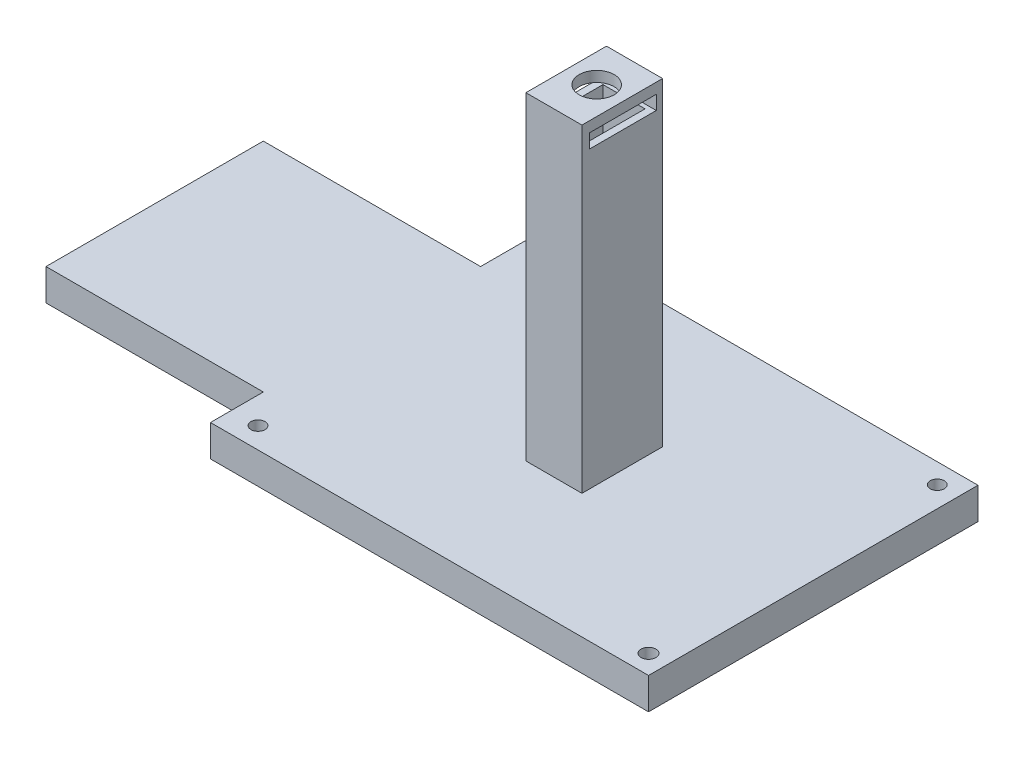
SolidWorks part; units mm, degrees
ref_plane "Front Plane" through (0, 0, 0) normal (0, 0, 1) x (1, 0, 0)
ref_plane "Top Plane" through (0, 0, 0) normal (0, 1, 0) x (1, 0, 0)
ref_plane "Right Plane" through (0, 0, 0) normal (1, 0, 0) x (0, 0, -1)
sketch "Sketch1" plane through (0, 0, 0) normal (0, 1, 0) x (1, 0, 0)
  line L1 (-61.7229, 30.9725) -> (63.2771, 30.9725)
  line L2 (-61.7229, 30.9725) -> (-61.7229, -63.0275)
  line L3 (-61.7229, -63.0275) -> (63.2771, -63.0275)
  line L4 (63.2771, 30.9725) -> (63.2771, -63.0275)
  dimension "D1" = 125
  dimension "D2" = 94
extrude "Boss-Extrude2" add sketch "Sketch1" along normal blind 9
sketch "Sketch2" plane through (0, 0, 0) normal (0, 1, 0) x (1, 0, 0)
  line L0 (63.2771, 30.9725) -> (-61.7229, 30.9725) construction
  line L1 (-7.2229, -4.5275) -> (8.7771, -4.5275)
  line L2 (-7.2229, -4.5275) -> (-7.2229, -27.5275)
  line L3 (-7.2229, -27.5275) -> (8.7771, -27.5275)
  line L4 (8.7771, -4.5275) -> (8.7771, -27.5275)
  line L5 (-61.7229, -63.0275) -> (63.2771, -63.0275) construction
  line L6 (-61.7229, 30.9725) -> (-61.7229, -63.0275) construction
  line L7 (63.2771, -63.0275) -> (63.2771, 30.9725) construction
  dimension "D1" = 16
  dimension "D2" = 23
  dimension "D3" = 35.5
  dimension "D4" = 35.5
  dimension "D5" = 54.5
  dimension "D6" = 54.5
extrude "Boss-Extrude4" add sketch "Sketch2" along normal blind 100
sketch "Sketch4" plane through (0, 0, 0) normal (0, 1, 0) x (1, 0, 0)
  line L0 (-7.2229, -27.5275) -> (8.7771, -27.5275) construction
  line L1 (-5.2229, -7.5275) -> (6.7771, -7.5275)
  line L2 (-5.2229, -7.5275) -> (-5.2229, -24.5275)
  line L3 (-5.2229, -24.5275) -> (6.7771, -24.5275)
  line L4 (6.7771, -7.5275) -> (6.7771, -24.5275)
  line L5 (-7.2229, -4.5275) -> (8.7771, -4.5275) construction
  line L6 (-7.2229, -4.5275) -> (-7.2229, -27.5275) construction
  line L7 (8.7771, -27.5275) -> (8.7771, -4.5275) construction
  point P4 (0.7771, -24.5275)
  dimension "D1" = 12
  dimension "D2" = 17
  dimension "D3" = 3
  dimension "D4" = 3
  dimension "D5" = 2
  dimension "D6" = 2
extrude "Cut-Extrude1" cut sketch "Sketch4" along normal blind 96.5
sketch "Sketch5" plane through (0, 100, 0) normal (0, 1, 0) x (1, 0, 0)
  circle A0 centre (0.9054, -15.4503) radius 5
  dimension "D1" = 10
extrude "Cut-Extrude2" cut sketch "Sketch5" against normal blind 100
sketch "Sketch6" plane through (0, 0, 0) normal (1, 0, 0) x (0, 0, -1)
  line L0 (-27.5275, 100) -> (-4.5275, 100) construction
  line L1 (-25.3235, 97) -> (-6.3235, 97)
  line L2 (-25.3235, 97) -> (-25.3235, 93)
  line L3 (-25.3235, 93) -> (-6.3235, 93)
  line L4 (-6.3235, 97) -> (-6.3235, 93)
  dimension "D1" = 19
  dimension "D2" = 3
  dimension "D3" = 4
extrude "Cut-Extrude3" cut sketch "Sketch6" against normal blind 100 from surface at 8.7771 starting at face at (8.7771, 54.5, 16.0275)
sketch "Sketch7" plane through (0, 0, 0) normal (0, 1, 0) x (1, 0, 0)
  line L0 (-61.7229, 30.9725) -> (-61.7229, -63.0275) construction
  line L1 (63.2771, 30.9725) -> (-61.7229, 30.9725) construction
  circle A0 centre (-54.5129, 25.8525) radius 2
  circle A1 centre (57.3357, 25.2881) radius 2.003
  circle A2 centre (57.8092, -57.5719) radius 2.1086
  circle A3 centre (-54.1694, -57.0075) radius 2.0004
  dimension "D1" = 4
  dimension "D2" = 7.21
  dimension "D3" = 5.12
  dimension "D4" = 111.85
  dimension "D5" = 82.86
  dimension "D6" = 111.98
  dimension "D7" = 82.86
extrude "Cut-Extrude4" cut sketch "Sketch7" along normal blind 100
sketch "Sketch8" plane through (0, 0, 0) normal (0, 1, 0) x (1, 0, 0)
  line L0 (-61.7229, 30.9725) -> (-61.7229, -63.0275) construction
  line L1 (-61.7229, -47.9475) -> (-123.7229, -47.9475)
  line L2 (-61.7229, -47.9475) -> (-61.7229, 14.0525)
  line L3 (-61.7229, 14.0525) -> (-123.7229, 14.0525)
  line L4 (-123.7229, -47.9475) -> (-123.7229, 14.0525)
  dimension "D1" = 62
  dimension "D2" = 62
  dimension "D3" = 62
extrude "Boss-Extrude5" add sketch "Sketch8" along normal blind 9
